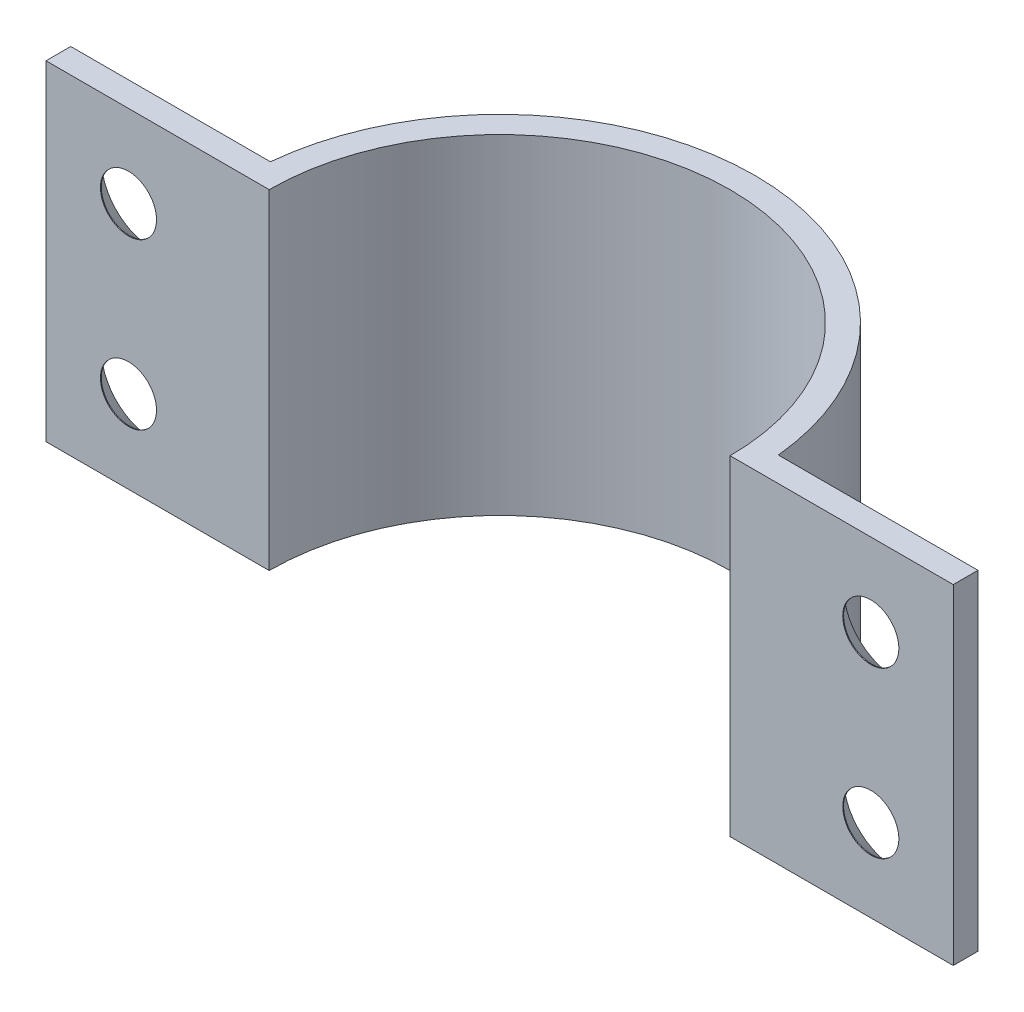
SolidWorks part; units mm, degrees
ref_plane "Front Plane" through (0, 0, 0) normal (0, 0, 1) x (1, 0, 0)
ref_plane "Top Plane" through (0, 0, 0) normal (0, 1, 0) x (1, 0, 0)
ref_plane "Right Plane" through (0, 0, 0) normal (1, 0, 0) x (0, 0, -1)
sketch "Sketch1" plane through (0, 0, 0) normal (0, 1, 0) x (1, 0, 0)
  line L0 (-13.97, 0) -> (-27.5, 0)
  line L1 (13.97, 0) -> (27.5, 0)
  line L2 (15.3971, 1.5) -> (27.5, 1.5)
  line L3 (-15.3971, 1.5) -> (-27.5, 1.5)
  line L4 (-27.5, 1.5) -> (-27.5, 0)
  line L5 (27.5, 1.5) -> (27.5, 0)
  arc A0 (13.97, 0) -> (-13.97, 0) centre (0, 0) ccw
  arc A1 (15.3971, 1.5) -> (-15.3971, 1.5) centre (0, 0) ccw
  dimension "D1" = 27.94
  dimension "D2" = 55
  dimension "D3" = 27.5
  dimension "D4" = 1.5
extrude "Boss-Extrude1" add sketch "Sketch1" along normal blind 20 contours L3 L4 L0 A0 L1 L5 L2 A1
sketch "Sketch2" plane through (0, 0, -1.5) normal (0, 0, -1) x (-1, 0, 0)
  line L0 (-27.5, 20) -> (-27.5, 0) construction
  line L1 (-15.3971, 0) -> (-27.5, 0) construction
  line L2 (27.5, 20) -> (27.5, 0) construction
  line L3 (15.3971, 0) -> (27.5, 0) construction
  line L4 (-15.3971, 20) -> (-27.5, 20) construction
  line L5 (15.3971, 20) -> (27.5, 20) construction
  point P0 (-22.5, 5)
  point P1 (22.5, 5)
  point P10 (-22.5, 15)
  point P11 (22.5, 15)
  dimension "D1" = 5
  dimension "D2" = 5
  dimension "D3" = 5
  dimension "D4" = 5
  dimension "D5" = 5
  dimension "D6" = 5
  dimension "D7" = 5
  dimension "D8" = 5
hole_wizard "CSK for M3 Countersunk Flat Head Screw1" positions "3DSketch1" profile "Sketch3" countersink size "M3" standard "ISO" end condition through all
sketch3d "3DSketch1"
  point P0 (22.5, 5, -1.5)
  point P3 (-22.5, 5, -1.5)
  point P6 (22.5, 15, -1.5)
  point P9 (-22.5, 15, -1.5)
sketch "Sketch3" plane through (22.5, 5, -1.5) normal (1, 0, 0) x (0, 1, 0)
  line L0 (0, 0) -> (0, 1.5)
  line L1 (0, 1.5) -> (1.7, 1.5)
  line L2 (1.7, 1.5) -> (1.7, 1.45)
  line L3 (1.7, 1.45) -> (3.15, 0)
  line L5 (3.15, 0) -> (0, 0)
  line L6 (-1.7, 1.45) -> (-3.15, 0) construction
  line L11 (0, -6.35) -> (0, 107.95) construction
  dimension "Thru Hole Dia." = 3.4
  dimension "Thru Hole Depth" = 1.5
  dimension "Near C'Sink Dia." = 6.3
  dimension "Near C'Sink Angle" = 90
